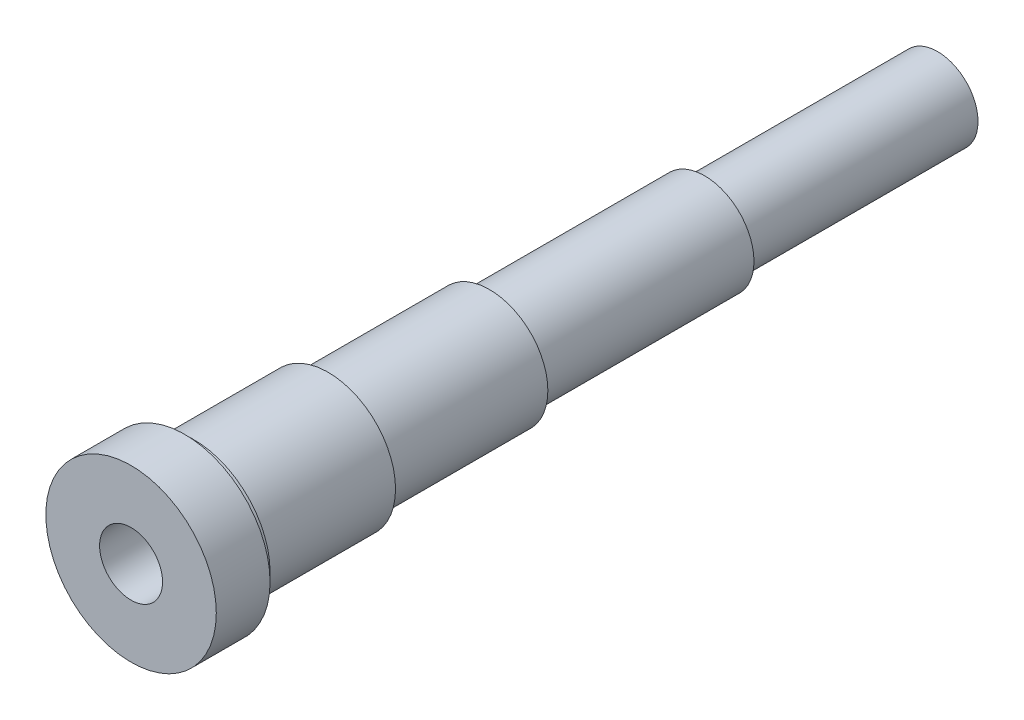
SolidWorks part; units mm, degrees
ref_plane "Front Plane" through (0, 0, 0) normal (0, 0, 1) x (1, 0, 0)
ref_plane "Top Plane" through (0, 0, 0) normal (0, 1, 0) x (1, 0, 0)
ref_plane "Right Plane" through (0, 0, 0) normal (1, 0, 0) x (0, 0, -1)
sketch "Sketch1" plane through (0, 0, 0) normal (1, 0, 0) x (0, 0, -1)
  line L0 (-238.175, 18.0848) -> (-238.175, -3.617)
  line L1 (-238.175, 18.0848) -> (-216.4733, 18.0848)
  line L2 (-216.4733, 18.0848) -> (-216.4733, 14.4678)
  line L3 (-216.4733, 14.4678) -> (-212.8563, 14.4678)
  line L4 (-212.8563, 14.4678) -> (-212.8563, 10.8509)
  line L5 (-212.8563, 10.8509) -> (-158.6019, 10.8509)
  line L6 (-158.6019, 10.8509) -> (-158.6019, 7.2339)
  line L7 (-158.6019, 7.2339) -> (-93.4966, 7.2339)
  line L8 (-93.4966, 7.2339) -> (-93.4966, 3.617)
  line L9 (-93.4966, 3.617) -> (-6.6896, 3.617)
  line L10 (-6.6896, 3.617) -> (-6.6896, 0)
  line L11 (-6.6896, 0) -> (87.3514, 0)
  line L12 (87.3514, 0) -> (87.3514, -3.617)
  line L13 (87.3514, -3.617) -> (-238.175, -3.617)
  line L14 (-254.8254, -16.317) -> (45.0363, -16.317) construction
  dimension "D1" = 3.617
  dimension "D2" = 3.617
  dimension "D3" = 3.617
  dimension "D4" = 3.617
  dimension "D5" = 3.617
  dimension "D6" = 3.617
  dimension "D7" = 325.5264
  dimension "D8" = 231.4854
  dimension "D9" = 144.6784
  dimension "D10" = 79.5731
  dimension "D11" = 25.3187
  dimension "D12" = 21.7018
  dimension "D13" = 12.7
revolve "Revolve1" add sketch "Sketch1" angle 360 about L14
